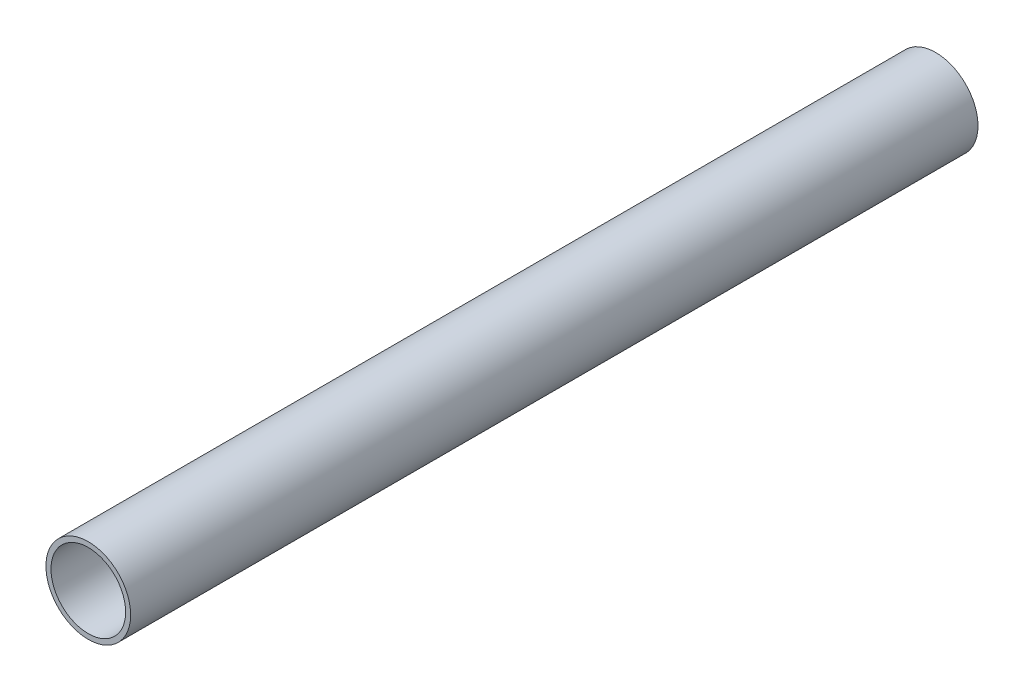
SolidWorks part; units mm, degrees
material "PE Высокой плотности"
ref_plane "Front" through (0, 0, 0) normal (0, 0, 1) x (1, 0, 0)
ref_plane "Top" through (0, 0, 0) normal (0, 1, 0) x (1, 0, 0)
ref_plane "Side" through (0, 0, 0) normal (1, 0, 0) x (0, 0, -1)
sketch "PipeSketch" plane through (0, 0, 0) normal (0, 0, 1) x (1, 0, 0)
  circle A0 centre (0, 0) radius 16
  circle A1 centre (0, 0) radius 14.1
  dimension "OuterDiameter" = 32
  dimension "InnerDiameter" = 28.2
extrude "Extrusion" add sketch "PipeSketch" along normal blind 320
sketch "FilterSketch" plane through (0, 0, 0) normal (0, 0, 1) x (1, 0, 0)
  circle A0 centre (0, 0) radius 16 construction
  dimension "NominalDiameter" = 32
